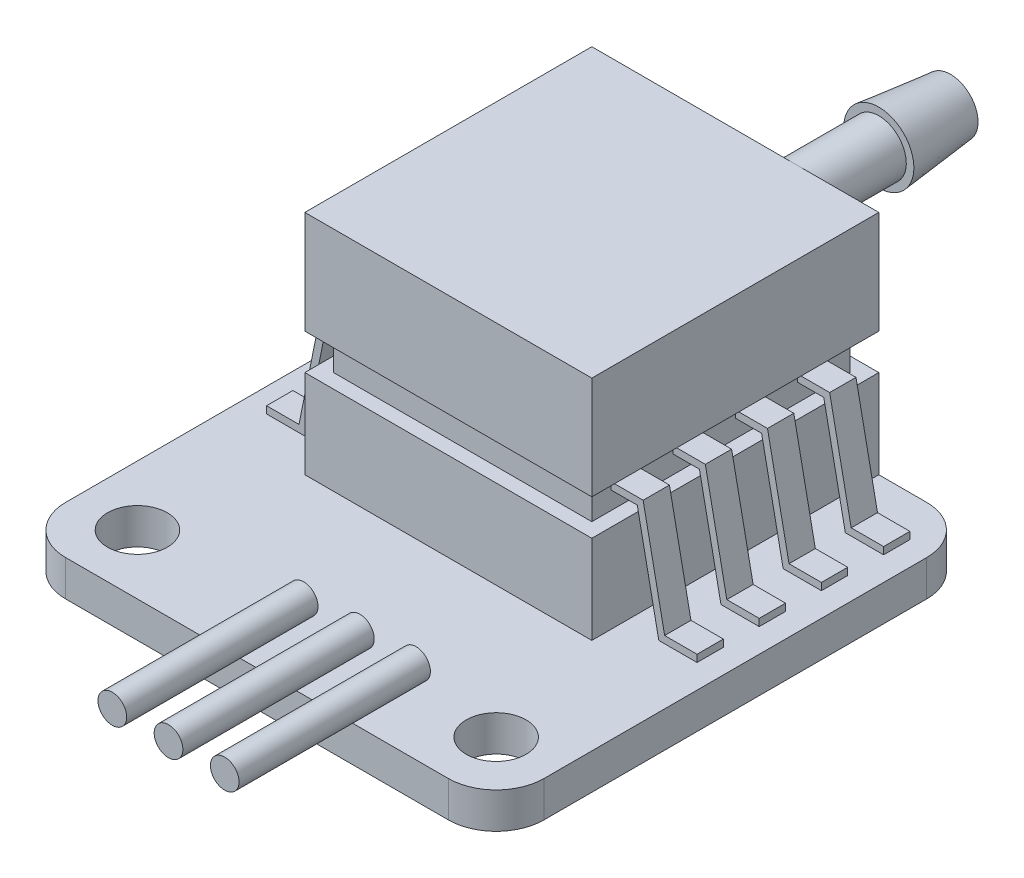
SolidWorks part; units mm, degrees
ref_plane "Спереди" through (0, 0, 0) normal (0, 0, 1) x (1, 0, 0)
ref_plane "Сверху" through (0, 0, 0) normal (0, 1, 0) x (1, 0, 0)
ref_plane "Справа" through (0, 0, 0) normal (1, 0, 0) x (0, 0, -1)
sketch "Эскиз1" plane through (0, 0, 0) normal (0, 1, 0) x (1, 0, 0)
  line L0 (2.5, 2.5) -> (17.5, 2.5) construction
  line L1 (2, 0) -> (18, 0)
  line L2 (0, 2) -> (0, 18)
  line L3 (2, 20) -> (18, 20)
  line L4 (20, 2) -> (20, 18)
  line L5 (10, 2.5) -> (10, 0) construction
  circle A0 centre (2.5, 2.5) radius 1.25
  circle A1 centre (17.5, 2.5) radius 1.25
  arc A2 (20, 2) -> (18, 0) centre (18, 2) cw
  arc A3 (2, 0) -> (0, 2) centre (2, 2) cw
  arc A4 (0, 18) -> (2, 20) centre (2, 18) cw
  arc A5 (18, 20) -> (20, 18) centre (18, 18) cw
  point P13 (0, 0)
  dimension "D3" = 2
  dimension "D5" = 2.5
  dimension "D1" = 20
  dimension "D2" = 20
  dimension "D4" = 15
  dimension "D6" = 2.5
extrude "Бобышка-Вытянуть1" add sketch "Эскиз1" along normal blind 1.5
sketch "Эскиз2" plane through (0, 1.5, 0) normal (0, 1, 0) x (1, 0, 0)
  line L0 (18, 20) -> (2, 20) construction
  line L1 (4, 20) -> (16, 20)
  line L2 (4, 20) -> (4, 8)
  line L3 (4, 8) -> (16, 8)
  line L4 (16, 20) -> (16, 8)
  line L5 (10, 20) -> (10, 8) construction
  dimension "D1" = 12
  dimension "D2" = 12
extrude "Бобышка-Вытянуть2" add sketch "Эскиз2" along normal blind 9.5
sketch "Эскиз3" plane through (0, 1.5, 0) normal (0, 1, 0) x (1, 0, 0)
  line L4 (10, 8) -> (10, 20) construction
  line L5 (15.4, 19.4) -> (4.6, 19.4)
  line L6 (15.4, 19.4) -> (15.4, 8.6)
  line L7 (15.4, 8.6) -> (4.6, 8.6)
  line L8 (4.6, 19.4) -> (4.6, 8.6)
  line L9 (4, 8) -> (16, 8) construction
  line L10 (16, 20) -> (4, 20) construction
  line L11 (4.6, 19.4) -> (15.4, 8.6) construction
  point P10 (10, 14)
  point P11 (10, 14)
  dimension "D1" = 10.8
  dimension "D2" = 10.8
extrude "Вырез-Вытянуть1" cut sketch "Эскиз3" along normal blind 1.5 from offset 3.7 flip side to cut
sketch "Эскиз4" plane through (0, 0, -20) normal (0, 0, -1) x (-1, 0, 0)
  line L0 (-16, 11) -> (-16, 6.7) construction
  line L1 (-16, 11) -> (-4, 11) construction
  line L2 (-4, 1.5) -> (-2, 1.5) construction
  line L3 (-4, 5.2) -> (-4, 1.5) construction
  circle A0 centre (-12.5, 9.85) radius 1.15
  circle A1 centre (-7.5, 2.65) radius 1.15
  circle A2 centre (-12.5, 9.85) radius 0.6
  circle A3 centre (-7.5, 2.65) radius 0.6
  dimension "D2" = 2.3
  dimension "D4" = 1.2
  dimension "D1" = 3.5
  dimension "D3" = 3.5
extrude "Бобышка-Вытянуть3" add sketch "Эскиз4" along normal blind 6.5
sketch "Эскиз5" plane through (0, 0, -26.5) normal (0, 0, -1) x (-1, 0, 0)
  circle A1 centre (-7.5, 2.65) radius 1.15 construction
  circle A2 centre (-7.5, 2.65) radius 1.15
  circle A3 centre (-12.5, 9.85) radius 1.15 construction
  circle A4 centre (-12.5, 9.85) radius 1.15
  circle A5 centre (-12.5, 9.85) radius 0.6 construction
  circle A6 centre (-12.5, 9.85) radius 0.6
  circle A7 centre (-7.5, 2.65) radius 0.6 construction
  circle A8 centre (-7.5, 2.65) radius 0.6
extrude "Бобышка-Вытянуть4" add sketch "Эскиз5" against normal blind 3 draft 6 draft outward yes
sketch "Эскиз6" plane through (0, 0, -20) normal (0, 0, -1) x (-1, 0, 0)
  line L0 (-17.4, 1.5) -> (-19, 1.5)
  line L1 (-18, 1.5) -> (-16, 1.5) construction
  line L2 (-17.4, 1.5) -> (-16.5, 5.95)
  line L3 (-16.5, 5.95) -> (-15.4, 5.95)
  line L4 (-10, 5.2) -> (-10, 1.5) construction
  line L5 (-16, 5.2) -> (-4, 5.2) construction
  line L6 (-3.5, 5.95) -> (-4.6, 5.95)
  line L7 (-2.6, 1.5) -> (-3.5, 5.95)
  line L8 (-2.6, 1.5) -> (-1, 1.5)
  line L9 (-15.4, 6.7) -> (-15.4, 5.2) construction
  dimension "D1" = 13
  dimension "D2" = 14.8
  dimension "D3" = 18
extrude "Вытянуть-Тонкостенный1" add sketch "Эскиз6" against normal blind 1.1 from offset 1.7 thin offset against normal yes
pattern_linear "Линейный массив1" count 4 spacing 2.6 along (0, 0, 1) of "Вытянуть-Тонкостенный1"
sketch "Эскиз7" plane through (0, 0, 0) normal (0, 0, 1) x (1, 0, 0)
  line L0 (8.95, 2) -> (13.65, 2) construction
  line L1 (2, 1.5) -> (18, 1.5) construction
  line L2 (20, 1.5) -> (20, 0) construction
  circle A0 centre (8.95, 2) radius 0.6
  circle A1 centre (11.3, 2) radius 0.6
  circle A2 centre (13.65, 2) radius 0.6
  dimension "D1" = 1.2
  dimension "D2" = 0.5
  dimension "D3" = 4.7
  dimension "D4" = 8.7
extrude "Бобышка-Вытянуть5" add sketch "Эскиз7" along normal blind 5 and the other way blind 3
